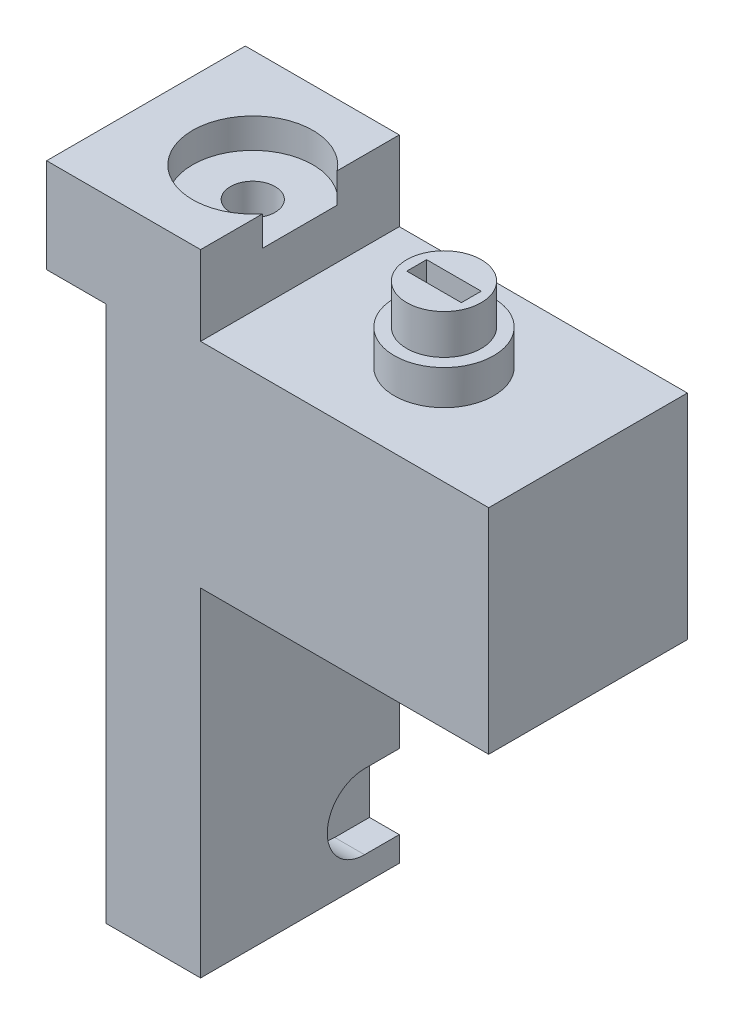
SolidWorks part; units mm, degrees
ref_plane "Front Plane" through (0, 0, 0) normal (0, 0, 1) x (1, 0, 0)
ref_plane "Top Plane" through (0, 0, 0) normal (0, 1, 0) x (1, 0, 0)
ref_plane "Right Plane" through (0, 0, 0) normal (1, 0, 0) x (0, 0, -1)
sketch "Sketch1" plane through (0, 0, 0) normal (0, 0, 1) x (1, 0, 0)
  line L0 (0, 0) -> (4.826, 0)
  line L1 (4.826, 0) -> (4.826, 32.258)
  line L2 (4.826, 32.258) -> (-3.048, 32.258)
  line L3 (-3.048, 32.258) -> (-3.048, 27.432)
  line L4 (-3.048, 27.432) -> (0, 27.432)
  line L5 (0, 27.432) -> (0, 0)
  line L6 (4.826, 28.194) -> (19.558, 28.194)
  line L7 (4.826, 17.272) -> (19.558, 17.272)
  line L8 (19.558, 17.272) -> (19.558, 28.194)
  dimension "D1" = 4.826
  dimension "D2" = 7.874
  dimension "D3" = 32.258
  dimension "D4" = 4.826
  dimension "D5" = 4.064
  dimension "D6" = 14.732
  dimension "D7" = 10.922
extrude "Boss-Extrude1" add sketch "Sketch1" against normal blind 10.16 contours L7 L8 L6 L1 | L4 L5 L0 L1 L2 L3
sketch "Sketch2" plane through (0, 0, 0) normal (0, -1, 0) x (-1, 0, 0)
  line L0 (0, 10.16) -> (-4.826, 10.16) construction
  line L1 (0, 10.16) -> (0, 0) construction
  line L2 (-2.413, 10.16) -> (-2.413, 0) construction
  line L3 (0, 0) -> (-4.826, 0) construction
  line L4 (-4.826, 5.08) -> (0, 5.08) construction
  line L5 (-4.826, 10.16) -> (-4.826, 0) construction
  circle A0 centre (-2.413, 5.08) radius 1.143
  dimension "D1" = 2.286
extrude "Cut-Extrude1" cut sketch "Sketch2" against normal through all
sketch "Sketch3" plane through (4.826, 0, 0) normal (1, 0, 0) x (0, 0, -1)
  line L0 (10.16, 1.27) -> (8.382, 1.27)
  line L1 (10.16, 0) -> (10.16, 17.272) construction
  line L2 (10.16, 0) -> (0, 0) construction
  line L3 (10.16, 1.27) -> (10.16, 5.08)
  line L4 (10.16, 5.08) -> (8.382, 5.08)
  arc A0 (8.382, 1.27) -> (8.382, 5.08) centre (8.382, 3.175) cw
  dimension "D1" = 1.778
  dimension "D2" = 1.27
  dimension "D3" = 3.81
extrude "Cut-Extrude2" cut sketch "Sketch3" against normal blind 1.524 contours A0 L4 L3 L0
sketch "Sketch4" plane through (0, 32.258, 0) normal (0, 1, 0) x (1, 0, 0)
sketch "Sketch5" plane through (0, 32.258, 0) normal (0, 1, 0) x (1, 0, 0)
  line L0 (4.826, 10.16) -> (4.826, 0) construction
  line L1 (4.826, 5.08) -> (4.826, 3.175)
  line L2 (4.826, 5.08) -> (4.826, 6.985)
  circle A0 centre (2.413, 5.08) radius 3.0743
  circle M1 centre (2.413, 5.08) radius 1.143
  line M3 (4.826, 0) -> (4.826, 10.16)
  dimension "D1" = 1.905
extrude "Cut-Extrude5" cut sketch "Sketch5" against normal blind 1.524 contours A0 M3 M1
sketch "Sketch6" plane through (0, 28.194, 0) normal (0, 1, 0) x (1, 0, 0)
  line L0 (4.826, 5.08) -> (19.558, 5.08) construction
  line L1 (4.826, 10.16) -> (4.826, 0) construction
  line L2 (19.558, 10.16) -> (19.558, 0) construction
  line L3 (12.192, 10.16) -> (12.192, 0) construction
  line L4 (4.826, 10.16) -> (19.558, 10.16) construction
  line L5 (4.826, 0) -> (19.558, 0) construction
  circle A0 centre (12.192, 5.08) radius 2.54
  dimension "D1" = 5.08
extrude "Boss-Extrude2" add sketch "Sketch6" along normal blind 1.778
sketch "Sketch7" plane through (0, 29.972, 0) normal (0, 1, 0) x (1, 0, 0)
  circle A0 centre (12.192, 5.08) radius 1.905
  dimension "D1" = 3.81
extrude "Boss-Extrude3" add sketch "Sketch7" along normal blind 2.032
sketch "Sketch9" plane through (0, 32.004, 0) normal (0, 1, 0) x (1, 0, 0)
  line L0 (14.097, 5.08) -> (10.287, 5.08) construction
  line L1 (12.192, 3.175) -> (12.192, 6.985) construction
  line L2 (10.795, 4.572) -> (13.589, 4.572)
  line L3 (10.795, 4.572) -> (10.795, 5.588)
  line L4 (13.589, 4.572) -> (13.589, 5.588)
  line L5 (10.795, 5.588) -> (13.589, 5.588)
  line L6 (10.795, 4.572) -> (13.589, 5.588) construction
  line L7 (13.589, 4.572) -> (10.795, 5.588) construction
  circle A0 centre (12.192, 5.08) radius 1.905 construction
  point P8 (12.192, 5.08)
  dimension "D1" = 2.794
  dimension "D2" = 1.016
extrude "Cut-Extrude6" cut sketch "Sketch9" against normal blind 2.032
